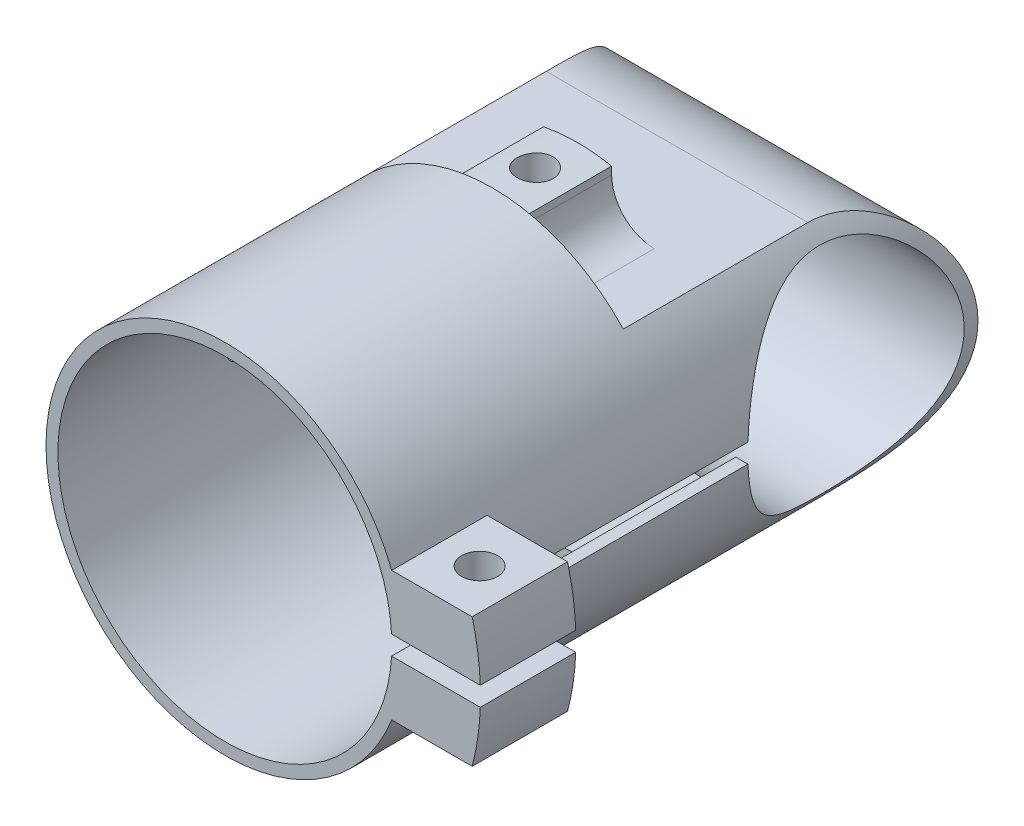
SolidWorks part; units mm, degrees
ref_plane "Front Plane" through (0, 0, 0) normal (0, 0, 1) x (1, 0, 0)
ref_plane "Top Plane" through (0, 0, 0) normal (0, 1, 0) x (1, 0, 0)
ref_plane "Right Plane" through (0, 0, 0) normal (1, 0, 0) x (0, 0, -1)
sketch "Sketch1" plane through (0, 0, 0) normal (1, 0, 0) x (0, 0, -1)
  line L0 (0, 0) -> (30.7601, 0) construction
  line L1 (0, 12.446) -> (0, 13.335)
  line L2 (0, 13.335) -> (42.799, 13.335)
  line L3 (42.799, 13.335) -> (42.799, 0)
  line L4 (42.799, 0) -> (19.05, 0)
  line L5 (19.05, 0) -> (19.05, 12.446)
  line L6 (19.05, 12.446) -> (0, 12.446)
  dimension "D1" = 42.799
  dimension "D2" = 19.05
  dimension "D3" = 0.889
  dimension "D4" = 12.446
revolve "Revolve1" add sketch "Sketch1" angle 360 about L0
sketch "Sketch3" plane through (0, 0, 0) normal (1, 0, 0) x (0, 0, -1)
  line L0 (42.799, -13.335) -> (42.799, 13.335) construction
  circle A0 centre (33.7058, 0) radius 8.0645
  dimension "D1" = 16.129
  dimension "D2" = 9.0932
extrude "Cut-Extrude1" cut sketch "Sketch3" against normal mid plane 30.48
sketch "Sketch5" plane through (0, 0, 0) normal (1, 0, 0) x (0, 0, -1)
  line L0 (33.7058, 9.0932) -> (19.939, 9.0932)
  line L1 (19.939, 9.0932) -> (19.939, 13.335)
  line L2 (33.7058, -9.0932) -> (19.939, -9.0932)
  line L3 (19.939, -9.0932) -> (19.939, -13.335)
  line L4 (0, -13.335) -> (42.799, -13.335) construction
  line L5 (19.939, -13.335) -> (43.7428, -13.335)
  line L6 (42.799, 13.335) -> (0, 13.335) construction
  line L7 (43.7428, 13.335) -> (19.939, 13.335)
  line L8 (43.7428, 13.335) -> (43.7428, -13.335)
  line L9 (0, 13.335) -> (0, -13.335) construction
  circle A0 centre (33.7058, 0) radius 8.0645 construction
  circle A1 centre (33.7058, 0) radius 8.0645 construction
  arc A2 (33.7058, -9.0932) -> (33.7058, 9.0932) centre (33.7058, 0) ccw
  circle A4 centre (33.7058, 0) radius 9.0932 construction
  point P16 (42.799, 0)
  dimension "D2" = 19.939
  dimension "D1" = 1.0287
extrude "Cut-Extrude2" cut sketch "Sketch5" against normal mid plane 30.48
sketch "Sketch6" plane through (0, 0, -19.05) normal (0, 0, 1) x (1, 0, 0)
  line L0 (-6.096, 0) -> (6.096, 0) construction
  line L1 (-6.096, 6.35) -> (6.096, 6.35)
  line L2 (-6.096, -6.35) -> (6.096, -6.35)
  arc A0 (-6.096, 6.35) -> (-6.096, -6.35) centre (-6.096, 0) ccw
  arc A1 (6.096, -6.35) -> (6.096, 6.35) centre (6.096, 0) ccw
  point P3 (0, 0)
  dimension "D1" = 6.35
  dimension "D2" = 12.192
  dimension "D3" = 6.096
extrude "Cut-Extrude3" cut sketch "Sketch6" against normal blind 12.7
sketch "Sketch7" plane through (0, 0, -19.939) normal (0, 0, -1) x (-1, 0, 0)
  line L0 (0, 14.4423) -> (0, 8.5733) construction
  line L2 (-5.715, 9.0932) -> (5.715, 9.0932)
  line L3 (-2.54, 12.832) -> (-2.54, 12.2682)
  line L4 (2.54, 12.832) -> (2.54, 12.2682)
  line L5 (-2.54, 14.4423) -> (-2.54, 8.5733) construction
  line L6 (2.54, 14.4423) -> (2.54, 8.5733) construction
  arc A0 (9.7538, 9.0932) -> (-9.7538, 9.0932) centre (0, 0) ccw construction
  arc A1 (9.7538, 9.0932) -> (-9.7538, 9.0932) centre (0, 0) ccw construction
  arc A2 (2.54, 12.832) -> (-2.54, 12.832) centre (0, 0) ccw
  arc A3 (9.568, 8.92) -> (-9.568, 8.92) centre (0, 0) ccw construction
  arc A4 (5.715, 9.0932) -> (2.54, 12.2682) centre (5.715, 12.2682) cw
  arc A5 (-2.54, 12.2682) -> (-5.715, 9.0932) centre (-5.715, 12.2682) cw
  dimension "D4" = 3.175
  dimension "D1" = 0.254
  dimension "D2" = 2.54
  dimension "D3" = 2.54
extrude "Boss-Extrude1" add sketch "Sketch7" along normal blind 6.35
sketch "Sketch8" plane through (0, 0, 0) normal (0, 1, 0) x (1, 0, 0)
  line L0 (-2.54, 26.289) -> (-2.54, 19.939) construction
  line L1 (-2.54, 26.289) -> (-2.54, 19.939) construction
  line L2 (2.54, 26.289) -> (2.54, 19.939) construction
  line L3 (2.54, 26.289) -> (2.54, 19.939) construction
  line L4 (-2.54, 23.114) -> (2.54, 23.114) construction
  circle A0 centre (0, 23.114) radius 1.3462
  dimension "D1" = 2.6924
extrude "Cut-Extrude4" cut sketch "Sketch8" against normal mid plane 29.21
sketch "Sketch9" plane through (0, 0, 0) normal (1, 0, 0) x (0, 0, -1)
  line L0 (28.6961, 0) -> (13.335, 0) construction
  line L1 (28.6961, 0.7112) -> (13.335, 0.7112)
  line L2 (28.6961, -0.7112) -> (13.335, -0.7112)
  line L3 (28.6961, 0.7112) -> (28.6961, -0.7112)
  arc A0 (13.335, 0.7112) -> (13.335, -0.7112) centre (13.335, 0) ccw
  dimension "D1" = 13.335
  dimension "D2" = 0.7112
extrude "Cut-Extrude5" cut sketch "Sketch9" against normal blind 29.21
sketch "Sketch10" plane through (0, 0, 0) normal (1, 0, 0) x (0, 0, -1)
  line L0 (0, 13.335) -> (0, -13.335) construction
  line L1 (0, 4.826) -> (0, -4.826)
  line L2 (7.112, 4.826) -> (7.112, -4.826)
  line L3 (-2.8814, 0) -> (28.0778, 0) construction
  line L4 (0, -4.826) -> (7.112, -4.826)
  line L5 (0, 4.826) -> (7.112, 4.826)
  line L6 (-2.8814, 4.826) -> (28.0778, 4.826) construction
  line L7 (0, 13.335) -> (0, -13.335) construction
  line L8 (7.112, 13.335) -> (7.112, -13.335) construction
  line L9 (-2.8814, -4.826) -> (28.0778, -4.826) construction
  dimension "D1" = 7.112
  dimension "D2" = 4.826
  dimension "D3" = 4.826
extrude "Boss-Extrude2" add sketch "Sketch10" along normal blind 19.05
sketch "Sketch11" plane through (0, 0, 0) normal (0, 0, 1) x (1, 0, 0)
  circle A0 centre (0, 0) radius 12.446
extrude "Cut-Extrude6" cut sketch "Sketch11" against normal blind 13.97
sketch "Sketch13" plane through (0, 0, 0) normal (0, 0, 1) x (1, 0, 0)
  line L0 (19.6899, 4.826) -> (19.6899, -4.826)
  line L1 (19.05, 4.826) -> (12.4311, 4.826) construction
  line L2 (19.6899, 4.826) -> (18.4286, 4.826)
  line L3 (19.05, -4.826) -> (12.4311, -4.826) construction
  line L4 (19.6899, -4.826) -> (18.4286, -4.826)
  arc A0 (18.4286, -4.826) -> (18.4286, 4.826) centre (0, 0) ccw
  dimension "D1" = 19.05
extrude "Cut-Extrude8" cut sketch "Sketch13" against normal blind 13.97
sketch "Sketch14" plane through (0, 4.826, 0) normal (0, 1, 0) x (1, 0, 0)
  line L0 (18.4286, 7.112) -> (12.4311, 7.112) construction
  line L1 (18.4286, 7.112) -> (12.4311, 7.112) construction
  line L2 (18.4286, 0) -> (12.4311, 0) construction
  line L3 (18.4286, 0) -> (12.4311, 0) construction
  line L4 (15.4298, 7.112) -> (15.4298, 0) construction
  circle A0 centre (15.4298, 3.556) radius 1.3462
  dimension "D1" = 2.6924
extrude "Cut-Extrude9" cut sketch "Sketch14" against normal blind 13.97
sketch "Sketch15" plane through (0, 0, 0) normal (1, 0, 0) x (0, 0, -1)
  line L0 (13.335, 0.7112) -> (19.05, 0.7112) construction
  line L1 (0, 0.7112) -> (25.6727, 0.7112)
  line L2 (19.05, -0.7112) -> (13.335, -0.7112) construction
  line L3 (25.6727, -0.7112) -> (0, -0.7112)
  line L4 (0, 13.335) -> (0, -13.335) construction
  line L5 (0, 0.7112) -> (0, -0.7112)
  circle A0 centre (33.7058, 0) radius 8.0645 construction
  arc A1 (25.6727, 0.7112) -> (25.6727, -0.7112) centre (33.7058, 0) ccw
extrude "Cut-Extrude10" cut sketch "Sketch15" along normal blind 21.59
sketch "Sketch16" plane through (0, 0, -19.05) normal (0, 0, 1) x (1, 0, 0)
  line L0 (0, 13.8014) -> (0, 9.5245) construction
  line L5 (-0.5715, 10.6417) -> (-0.5715, 10.3677)
  line L6 (0.5715, 10.6417) -> (0.5715, 10.3677)
  line L7 (-15.3912, 0) -> (24.3617, 0) construction
  line L10 (-0.5715, 10.3677) -> (0.5715, 10.3677)
  arc A0 (12.4257, 0.7112) -> (12.4257, -0.7112) centre (0, 0) ccw construction
  arc A1 (2.4746, 12.1975) -> (-2.4746, 12.1975) centre (0, 0) ccw
  arc A3 (2.4746, 12.1975) -> (0.5715, 10.6417) centre (2.159, 10.6417) ccw
  arc A4 (-0.5715, 10.6417) -> (-2.4746, 12.1975) centre (-2.159, 10.6417) ccw
  dimension "D5" = 1.5875
extrude "Boss-Extrude3" add sketch "Sketch16" along normal blind 2.54
scale "Scale1" scale about centroid uniform scaling yes scale factor 0.6
